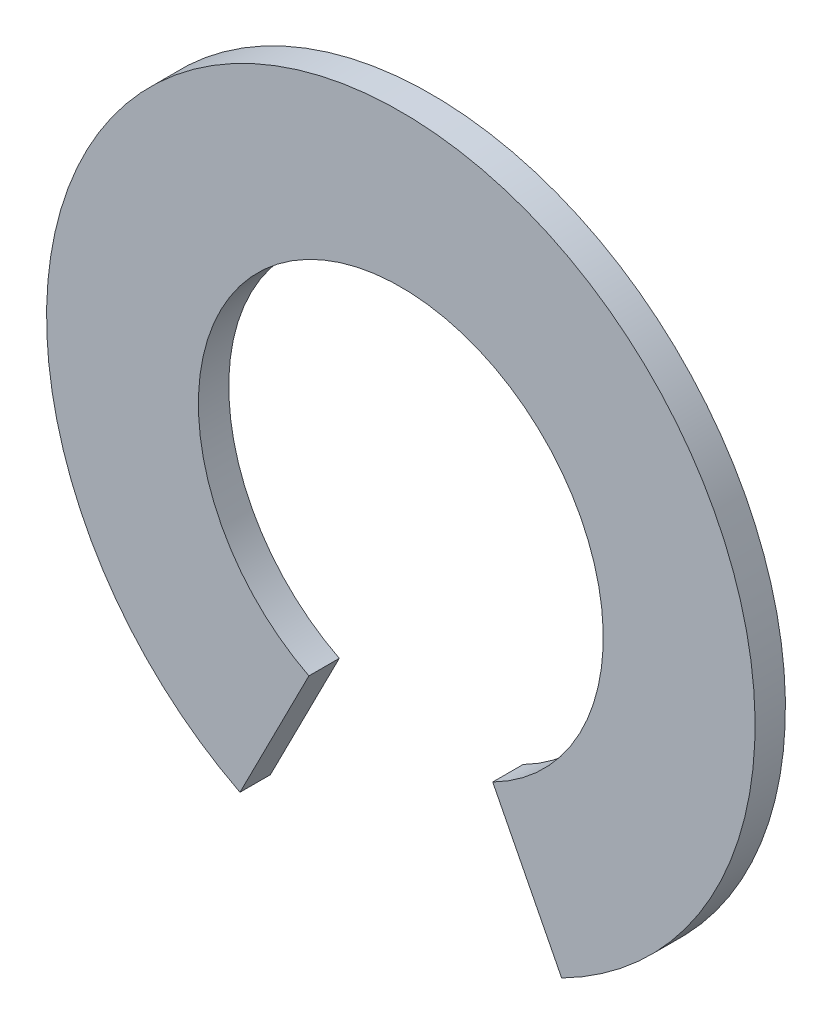
SolidWorks part; units mm, degrees
ref_plane "Спереди" through (0, 0, 0) normal (0, 0, 1) x (1, 0, 0)
ref_plane "Сверху" through (0, 0, 0) normal (0, 1, 0) x (1, 0, 0)
ref_plane "Справа" through (0, 0, 0) normal (1, 0, 0) x (0, 0, -1)
sketch "Sketch1" plane through (0, 0, 0) normal (0, 0, 1) x (1, 0, 0)
  line L1 (-4.5399, -8.9101) -> (-7.9448, -15.5926)
  line L2 (4.5399, -8.9101) -> (7.9448, -15.5926)
  arc A0 (4.5399, -8.9101) -> (-4.5399, -8.9101) centre (0, 0) ccw
  arc A1 (7.9448, -15.5926) -> (-7.9448, -15.5926) centre (0, 0) ccw
  point P34 (0, 0)
  dimension "D1" = 20
  dimension "D2" = 35
extrude "Boss-Extrude1" add sketch "Sketch1" along normal blind 1.5
